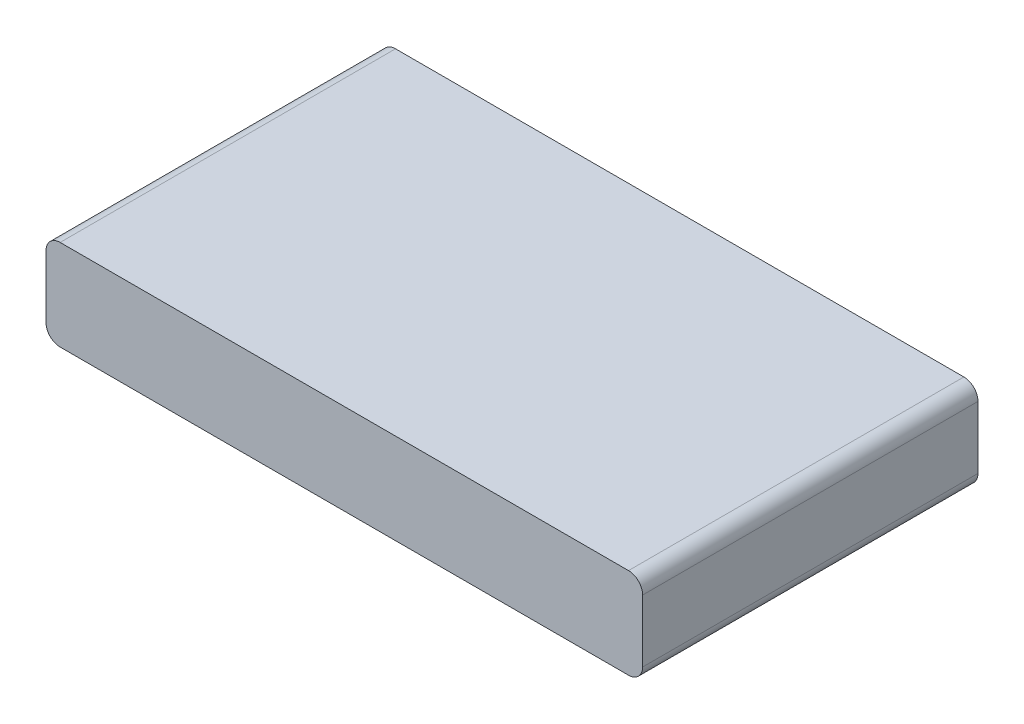
SolidWorks part; units mm, degrees
ref_plane "Front Plane" through (0, 0, 0) normal (0, 0, 1) x (1, 0, 0)
ref_plane "Top Plane" through (0, 0, 0) normal (0, 1, 0) x (1, 0, 0)
ref_plane "Right Plane" through (0, 0, 0) normal (1, 0, 0) x (0, 0, -1)
sketch "Sketch1" plane through (0, 0, 0) normal (0, 1, 0) x (1, 0, 0)
  line L1 (0, 0) -> (126.75, 0)
  line L2 (0, 0) -> (0, 71.25)
  line L3 (0, 71.25) -> (126.75, 71.25)
  line L4 (126.75, 0) -> (126.75, 71.25)
  dimension "D1" = 71.25
  dimension "D2" = 126.75
extrude "Boss-Extrude1" add sketch "Sketch1" along normal blind 19.25
fillet "Fillet2" radius 3 4 edges at (126.75, 0, -35.625) (126.75, 19.25, -35.625) (0, 0, -35.625) (0, 19.25, -35.625)
